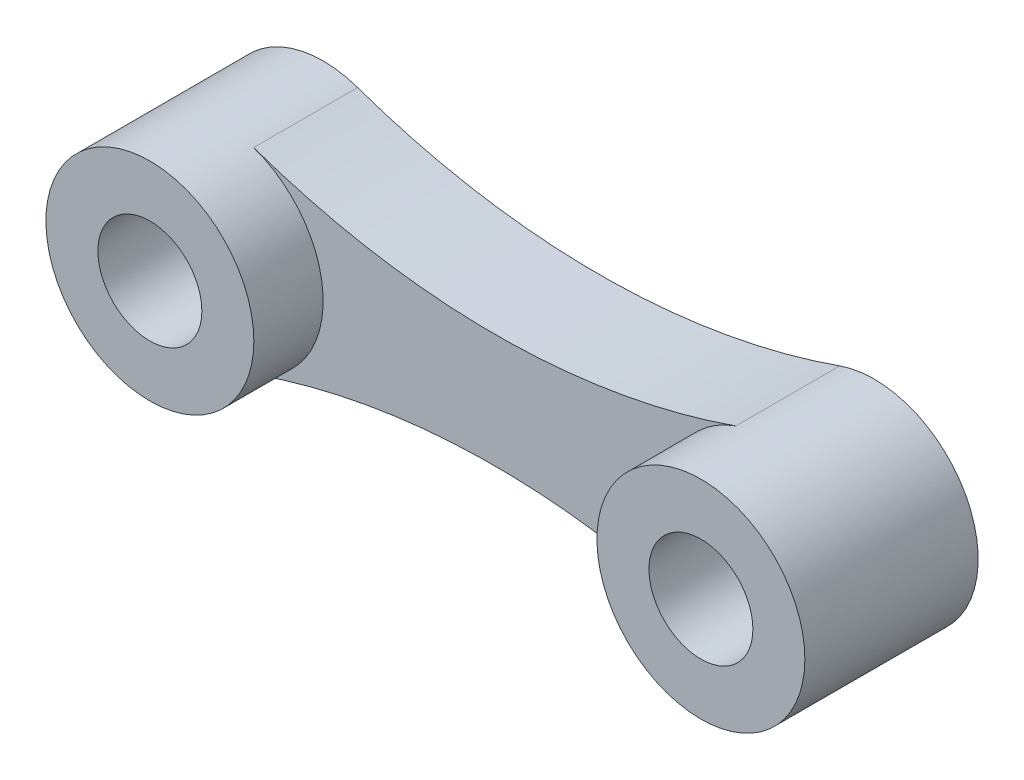
SolidWorks part; units mm, degrees
material "PVC 0.007 Plasticized"
ref_plane "Front Plane" through (0, 0, 0) normal (0, 0, 1) x (1, 0, 0)
ref_plane "Top Plane" through (0, 0, 0) normal (0, 1, 0) x (1, 0, 0)
ref_plane "Right Plane" through (0, 0, 0) normal (1, 0, 0) x (0, 0, -1)
sketch "Sketch1" plane through (0, 0, 0) normal (0, 0, 1) x (1, 0, 0)
  line L0 (-7.95, 0) -> (7.95, 0) construction
  line L1 (-7.95, 3) -> (7.95, 3)
  line L2 (-7.95, -3) -> (7.95, -3)
  circle A0 centre (-7.95, 0) radius 1.5
  circle A1 centre (7.95, 0) radius 1.5
  arc A2 (-7.95, 3) -> (-7.95, -3) centre (-7.95, 0) ccw
  arc A3 (7.95, -3) -> (7.95, 3) centre (7.95, 0) ccw
  point P3 (0, 0)
  dimension "D2" = 3
  dimension "D3" = 3
  dimension "D4" = 6
  dimension "D5" = 6
  dimension "D1" = 15.9
extrude "Boss-Extrude1" add sketch "Sketch1" along normal mid plane 3
sketch "Sketch2" plane through (0, 0, 1.5) normal (0, 0, 1) x (1, 0, 0)
  line L0 (0, 3) -> (0, -3) construction
  line L1 (7.95, 3) -> (-7.95, 3) construction
  line L2 (-7.95, -3) -> (7.95, -3) construction
  arc A6 (-6.9562, 2.8306) -> (-6.9562, -2.8306) centre (-7.95, 0) ccw
  arc A7 (6.9563, 2.8306) -> (6.9563, -2.8306) centre (7.95, 0) cw
  arc A8 (-6.9562, 2.8306) -> (6.9563, 2.8306) centre (0, 22.645) ccw
  arc A9 (-6.9562, -2.8306) -> (6.9563, -2.8306) centre (0, -22.645) cw
  point P7 (7.95, 0)
  point P8 (0, 0)
  point P9 (0, 0)
  point P20 (-6.9562, -2.6982)
  point P21 (0, 0)
  point P22 (6.9563, -2.6982)
  dimension "D1" = 21
  dimension "D2" = 3
  dimension "D4" = 21
  dimension "D3" = 0.9938
extrude "Cut-Extrude1" cut sketch "Sketch2" against normal up to next flip side to cut
sketch "Sketch3" plane through (0, 0, 1.5) normal (0, 0, 1) x (1, 0, 0)
  circle A0 centre (-7.95, 0) radius 1.5
  circle A1 centre (7.95, 0) radius 1.5
  circle A2 centre (-7.95, 0) radius 3
  circle A3 centre (7.95, 0) radius 3
  dimension "D1" = 3
  dimension "D2" = 6
  dimension "D3" = 6
extrude "Boss-Extrude2" add sketch "Sketch3" along normal blind 2
